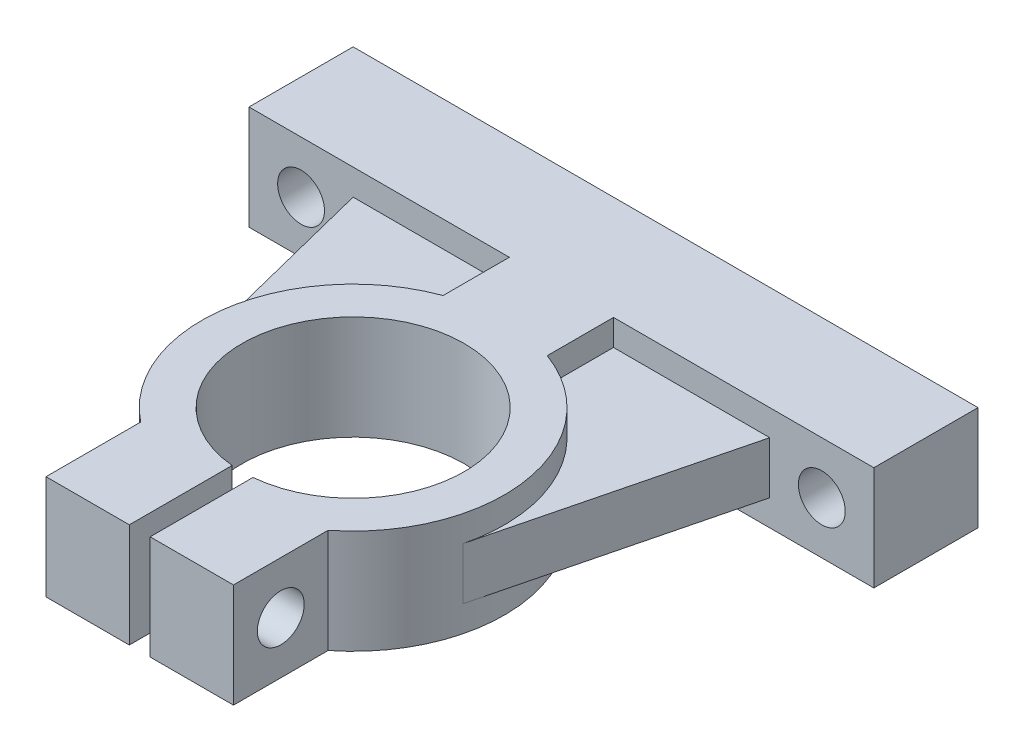
SolidWorks part; units mm, degrees
material "ABS"
ref_plane "Alzado" through (0, 0, 0) normal (0, 0, 1) x (1, 0, 0)
ref_plane "Planta" through (0, 0, 0) normal (0, 1, 0) x (1, 0, 0)
ref_plane "Vista lateral" through (0, 0, 0) normal (1, 0, 0) x (0, 0, -1)
sketch "Croquis1" plane through (0, 0, 0) normal (0, 1, 0) x (1, 0, 0)
  line L0 (0, 0) -> (0, -30) construction
  line L1 (30, 0) -> (-30, 0)
  line L2 (-30, 0) -> (-30, -10)
  line L3 (-30, -10) -> (-5, -10)
  line L4 (-5, -10) -> (-5, -16.3627)
  line L5 (30, 0) -> (30, -10)
  line L6 (30, -10) -> (5, -10)
  line L7 (5, -10) -> (5, -16.3627)
  arc A0 (-5, -16.3627) -> (5, -16.3627) centre (0, -30) ccw
  circle A1 centre (0, -30) radius 10.668
  point P7 (0, 0)
  dimension "D1" = 29.05
  dimension "D2" = 21.336
  dimension "D3" = 10
  dimension "D4" = 60
  dimension "D5" = 30
  dimension "D6" = 5
  dimension "D7" = 10
extrude "Saliente-Extruir1" add sketch "Croquis1" along normal mid plane 10
sketch "Croquis2" plane through (0, 0, 0) normal (0, 0, -1) x (-1, 0, 0)
  line L0 (-30, 0) -> (-25, 0) construction
  line L1 (-30, 5) -> (-30, -5) construction
  line L2 (-25, 0) -> (0, 0) construction
  line L3 (0, 0) -> (25, 0) construction
  line L4 (25, 0) -> (30, 0) construction
  line L5 (30, 5) -> (30, -5) construction
  circle A0 centre (25, 0) radius 2.25
  circle A1 centre (-25, 0) radius 2.25
  dimension "D2" = 4.5
  dimension "D1" = 5
extrude "Cortar-Extruir1" cut sketch "Croquis2" against normal up to next
sketch "Croquis3" plane through (0, 0, 0) normal (0, 1, 0) x (1, 0, 0)
  line L0 (-20, -10) -> (-14.0874, -33.5386)
  line L1 (-30, -10) -> (-5, -10) construction
  line L2 (-5, -10) -> (-5, -16.3627) construction
  line L3 (-20, -10) -> (-5, -10)
  line L4 (-5, -10) -> (-5, -16.3627)
  line L5 (0, -5.5) -> (0, 5.5) construction
  line L6 (20, -10) -> (5, -10)
  line L7 (20, -10) -> (14.0874, -33.5386)
  line L8 (5, -10) -> (5, -16.3627)
  arc A0 (-5, -16.3627) -> (5, -16.3627) centre (0, -30) ccw construction
  arc A1 (-5, -16.3627) -> (-14.0874, -33.5386) centre (0, -30) ccw
  arc A2 (5, -16.3627) -> (14.0874, -33.5386) centre (0, -30) cw
  dimension "D1" = 15
extrude "Saliente-Extruir2" add sketch "Croquis3" along normal mid plane 5 contours A1 L4 L3 L0 | L8 A2 L7 L6
ref_plane "Plano1" through (0, 0, 44.525) normal (0, 0, 1) x (1, 0, 0)
sketch "Croquis7" plane through (0, 5, 0) normal (0, 1, 0) x (1, 0, 0)
  line L0 (0, -40.668) -> (0, -44.525) construction
  line L2 (1, -46.5965) -> (-1, -46.5965)
  line L3 (1, -46.5965) -> (1, -38.5965)
  line L4 (1, -38.5965) -> (-1, -38.5965)
  line L5 (-1, -46.5965) -> (-1, -38.5965)
  line L6 (1, -46.5965) -> (-1, -38.5965) construction
  line L7 (1, -38.5965) -> (-1, -46.5965) construction
  circle A0 centre (0, -30) radius 10.668 construction
  arc A1 (-5, -16.3627) -> (5, -16.3627) centre (0, -30) ccw construction
  point P7 (0, -42.5965)
  dimension "D1" = 2
  dimension "D2" = 8
extrude "Cortar-Extruir5" cut sketch "Croquis7" against normal through all
sketch "Croquis8" plane through (0, 5, 0) normal (0, 1, 0) x (1, 0, 0)
  line L0 (-1, -44.4905) -> (-1, -50.4905)
  line L1 (-1, -50.4905) -> (-9, -50.4905)
  line L2 (-9, -50.4905) -> (-9, -41.4007)
  line L3 (0, -5.5) -> (0, 5.5) construction
  line L4 (9, -50.4905) -> (9, -41.4007)
  line L5 (1, -50.4905) -> (9, -50.4905)
  line L6 (1, -44.4905) -> (1, -50.4905)
  arc A0 (-5, -16.3627) -> (-1, -44.4905) centre (0, -30) ccw construction
  arc A1 (-9, -41.4007) -> (-1, -44.4905) centre (0, -30) ccw
  arc A2 (9, -41.4007) -> (1, -44.4905) centre (0, -30) cw
  dimension "D1" = 8
  dimension "D2" = 6
extrude "Saliente-Extruir3" add sketch "Croquis8" against normal up to surface (10 mm away) up to face at (0, -5, 18.7414)
sketch "Croquis9" plane through (9, 0, 0) normal (1, 0, 0) x (0, 0, -1)
  line L0 (-45.9456, 5) -> (-45.9456, -5) construction
  line L1 (-50.4905, 5) -> (-41.4007, 5) construction
  line L2 (-41.4007, -5) -> (-50.4905, -5) construction
  circle A0 centre (-45.9456, 0) radius 2.25
  dimension "D1" = 4.5
extrude "Cortar-Extruir6" cut sketch "Croquis9" against normal up to surface (18 mm away) up to face at (-9, 0, 45.9456)
